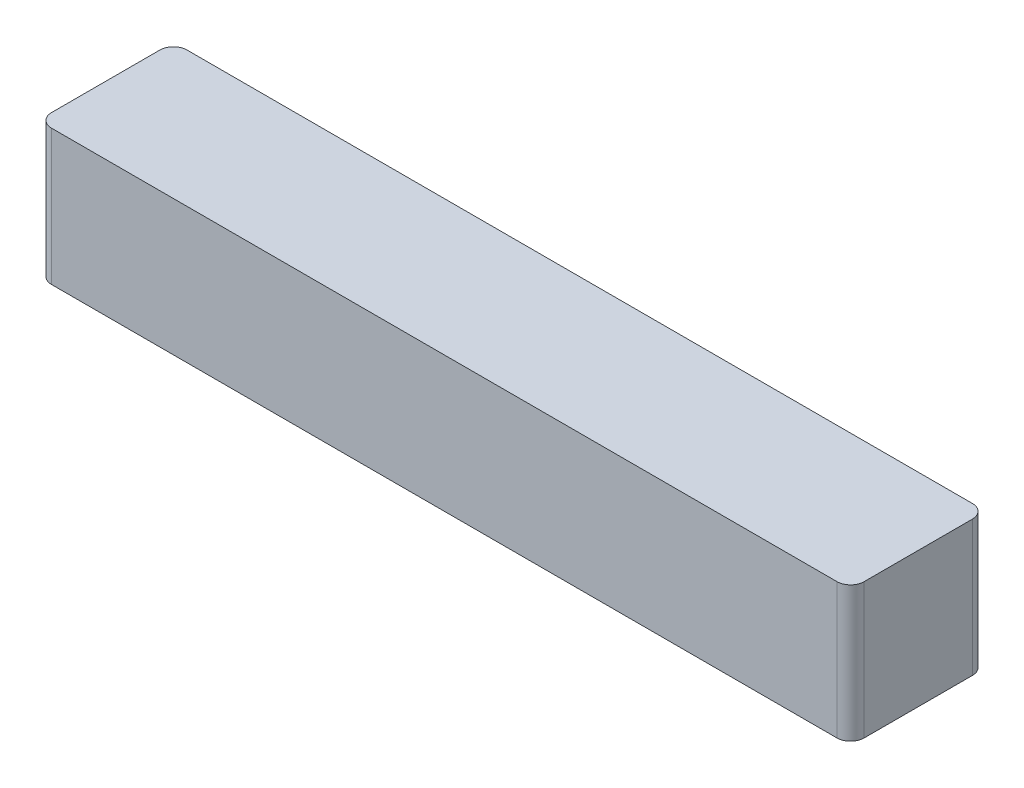
SolidWorks part; units mm, degrees
material "Acrylic (Medium-high impact)"
ref_plane "Front Plane" through (0, 0, 0) normal (0, 0, 1) x (1, 0, 0)
ref_plane "Top Plane" through (0, 0, 0) normal (0, 1, 0) x (1, 0, 0)
ref_plane "Right Plane" through (0, 0, 0) normal (1, 0, 0) x (0, 0, -1)
sketch "Sketch1" plane through (0, 0, 0) normal (0, 1, 0) x (1, 0, 0)
  line L1 (0, 0) -> (38.1, 0)
  line L2 (0, 0) -> (0, 6.35)
  line L3 (0, 6.35) -> (38.1, 6.35)
  line L4 (38.1, 0) -> (38.1, 6.35)
  dimension "D1" = 6.35
  dimension "D2" = 38.1
extrude "Boss-Extrude1" add sketch "Sketch1" along normal blind 6.35
sketch "Sketch2" plane through (0, 0, 0) normal (-1, 0, 0) x (0, 0, 1)
  line L0 (-6.35, 0) -> (0, 6.35) construction
  line L1 (0, 6.35) -> (-6.35, 6.35) construction
  line L2 (-6.35, 6.35) -> (0, 0) construction
  circle A0 centre (-3.175, 3.175) radius 2.4003
  dimension "D1" = 4.8006
extrude "Cut-Extrude1" cut sketch "Sketch2" against normal blind 8.89
fillet "Fillet1" radius 0.635 4 edges at (0, 3.175, 0) (0, 3.175, -6.35) (38.1, 3.175, -6.35) (38.1, 3.175, 0)
sketch "Sketch3" plane through (0, 0, 0) normal (0, -1, 0) x (1, 0, 0)
  line L0 (0, -3.175) -> (38.1, -3.175) construction
  line L1 (0, -5.715) -> (0, -0.635) construction
  line L2 (38.1, -0.635) -> (38.1, -5.715) construction
  line L3 (38.1, -3.175) -> (19.05, 0) construction
  line L4 (0.635, 0) -> (37.465, 0) construction
  line L5 (19.05, 0) -> (19.05, -6.35) construction
  line L6 (37.465, -6.35) -> (0.635, -6.35) construction
  circle A0 centre (11.43, -3.175) radius 0.889
  circle A1 centre (26.67, -3.175) radius 0.889
  dimension "D1" = 1.778
  dimension "D2" = 7.62
extrude "Cut-Extrude2" cut sketch "Sketch3" against normal blind 3.81
